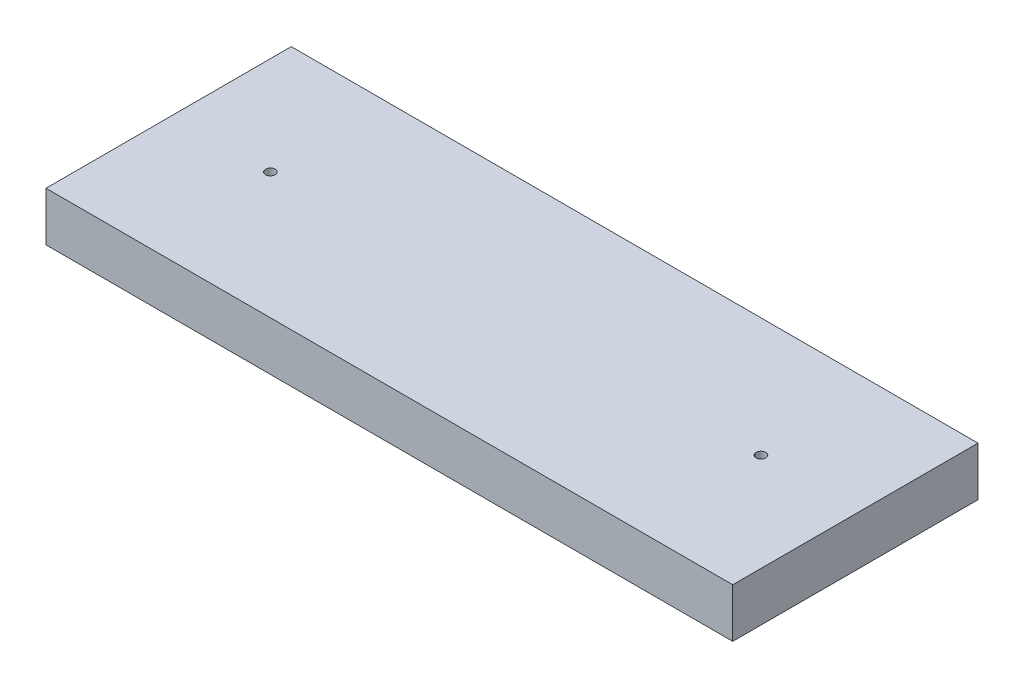
SolidWorks part; units mm, degrees
ref_plane "Front Plane" through (0, 0, 0) normal (0, 0, 1) x (1, 0, 0)
ref_plane "Top Plane" through (0, 0, 0) normal (0, 1, 0) x (1, 0, 0)
ref_plane "Right Plane" through (0, 0, 0) normal (1, 0, 0) x (0, 0, -1)
sketch "Sketch1" plane through (0, 0, 0) normal (0, 1, 0) x (1, 0, 0)
  line L1 (355.6, -127) -> (-355.6, -127)
  line L2 (355.6, -127) -> (355.6, 127)
  line L3 (355.6, 127) -> (-355.6, 127)
  line L4 (-355.6, -127) -> (-355.6, 127)
  line L5 (355.6, -127) -> (-355.6, 127) construction
  line L6 (355.6, 127) -> (-355.6, -127) construction
  point P0 (0, 0)
  dimension "D1" = 711.2
  dimension "D2" = 254
extrude "Boss-Extrude1" add sketch "Sketch1" along normal blind 50.8 contours L4 L3 L2 L1
hole_wizard "Ø10.0mm Dowel Hole1" positions "Sketch2" profile "Sketch3" hole size "Ø10.0" standard "ANSI Metric" end condition through all
sketch "Sketch2" plane through (0, 50.8, 0) normal (0, 1, 0) x (1, 0, 0)
  line L1 (-355.6, -127) -> (-355.6, 127) construction
  line L2 (355.6, -127) -> (355.6, 127) construction
  line L3 (-254, 3.81) -> (254, 3.81) construction
  line L5 (355.6, -127) -> (-355.6, -127) construction
  point P0 (-254, 3.81)
  point P2 (254, 3.81)
  dimension "D1" = 101.6
  dimension "D2" = 101.6
  dimension "D3" = 130.81
sketch "Sketch3" plane through (-254, 50.8, -3.81) normal (1, 0, 0) x (0, 0, 1)
  line L0 (0, 0) -> (0, 50.8)
  line L1 (0, 50.8) -> (5, 50.8)
  line L2 (5, 50.8) -> (5, 0)
  line L5 (5, 0) -> (0, 0)
  line L11 (0, -6.35) -> (0, 107.95) construction
  dimension "Thru Hole Dia." = 10
  dimension "Thru Hole Depth" = 50.8
